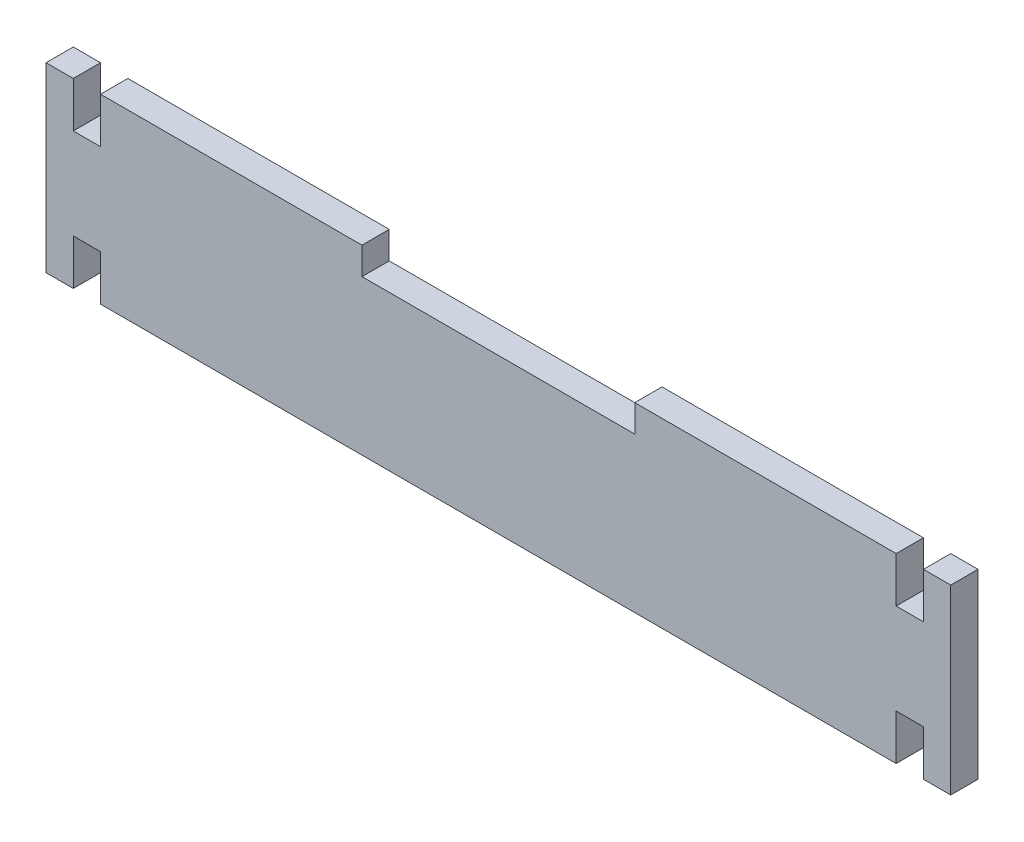
SolidWorks part; units mm, degrees
ref_plane "Front" through (0, 0, 0) normal (0, 0, 1) x (1, 0, 0)
ref_plane "Top" through (0, 0, 0) normal (0, 1, 0) x (1, 0, 0)
ref_plane "Right" through (0, 0, 0) normal (1, 0, 0) x (0, 0, -1)
sketch "Sketch1" plane through (0, 0, 0) normal (0, 0, 1) x (1, 0, 0)
  line L1 (0, 0) -> (-199, 0)
  line L2 (0, 0) -> (0, 40)
  line L3 (0, 40) -> (-199, 40)
  line L4 (-199, 0) -> (-199, 40)
  dimension "D1" = 40
  dimension "D2" = 199
extrude "Boss-Extrude1" add sketch "Sketch1" along normal blind 6
sketch "Sketch2" plane through (0, 0, 6) normal (0, 0, 1) x (1, 0, 0)
  line L0 (0, 40) -> (-199, 40) construction
  line L1 (-193, 40) -> (-187, 40)
  line L2 (-193, 40) -> (-193, 30)
  line L3 (-193, 30) -> (-187, 30)
  line L4 (-187, 40) -> (-187, 30)
  line L5 (-199, 40) -> (-199, 0) construction
  dimension "D1" = 10
  dimension "D2" = 6
  dimension "D3" = 6
extrude "Cut-Extrude1" cut sketch "Sketch2" against normal through all
pattern_linear "LPattern1" count 2 spacing 181 along (1, 0, 0) count 2 spacing 30 along (0, -1, 0) of "Cut-Extrude1"
sketch "Sketch3" plane through (0, 0, 6) normal (0, 0, 1) x (1, 0, 0)
  line L0 (-12, 40) -> (-187, 40) construction
  line L1 (-129.5, 40) -> (-69.5, 40)
  line L2 (-129.5, 40) -> (-129.5, 34)
  line L3 (-129.5, 34) -> (-69.5, 34)
  line L4 (-69.5, 40) -> (-69.5, 34)
  point P6 (-99.5, 40)
  point P7 (-99.5, 40)
  dimension "D1" = 60
  dimension "D2" = 6
extrude "Cut-Extrude2" cut sketch "Sketch3" against normal through all
